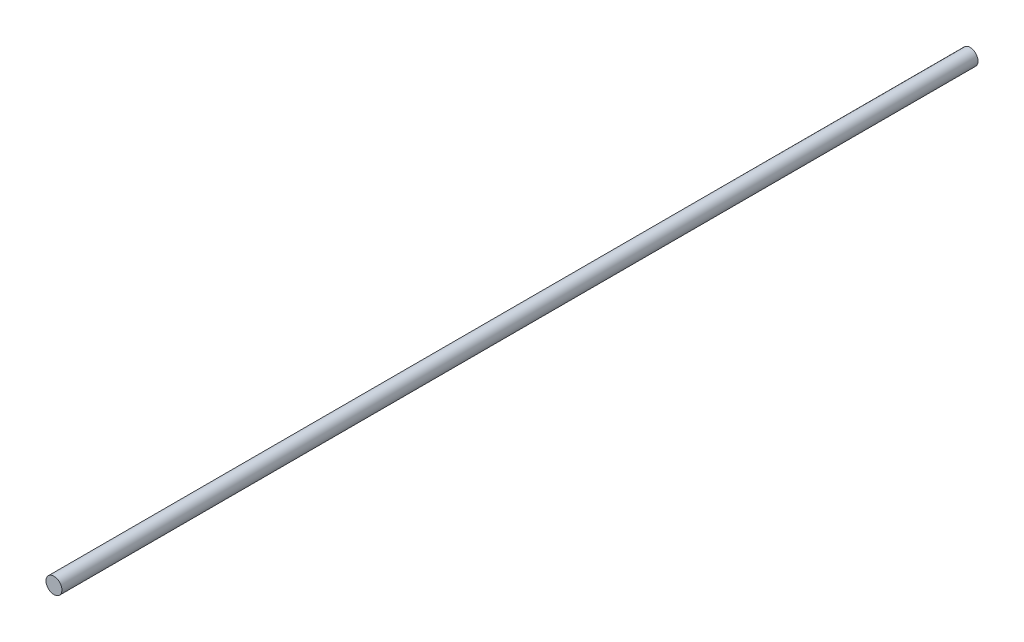
SolidWorks part; units mm, degrees
ref_plane "Front Plane" through (0, 0, 0) normal (0, 0, 1) x (1, 0, 0)
ref_plane "Top Plane" through (0, 0, 0) normal (0, 1, 0) x (1, 0, 0)
ref_plane "Right Plane" through (0, 0, 0) normal (1, 0, 0) x (0, 0, -1)
sketch "Sketch1" plane through (0, 0, 0) normal (0, 0, 1) x (1, 0, 0)
  circle A0 centre (0, 0) radius 4
  dimension "D1" = 8
extrude "Boss-Extrude1" add sketch "Sketch1" along normal blind 460
